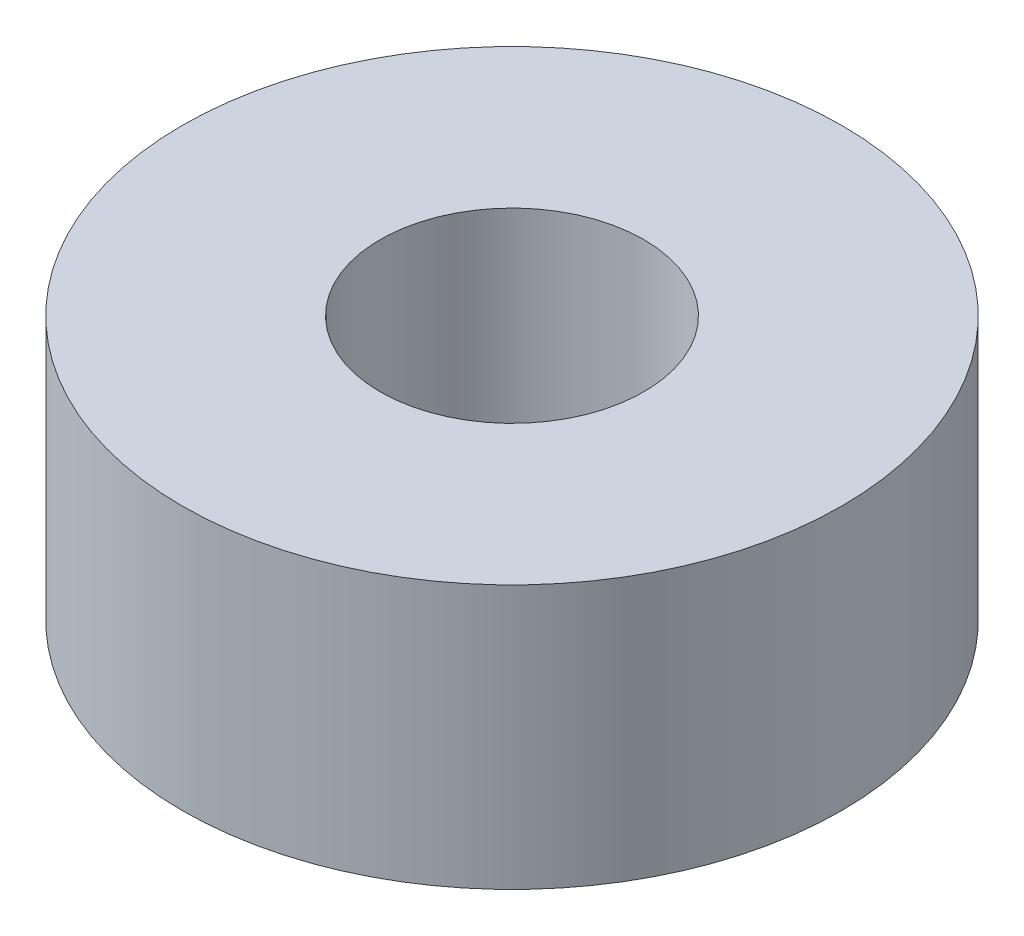
SolidWorks part; units mm, degrees
ref_plane "前视基准面" through (0, 0, 0) normal (0, 0, 1) x (1, 0, 0)
ref_plane "上视基准面" through (0, 0, 0) normal (0, 1, 0) x (1, 0, 0)
ref_plane "右视基准面" through (0, 0, 0) normal (1, 0, 0) x (0, 0, -1)
sketch "草图1" plane through (0, 0, 0) normal (0, 1, 0) x (1, 0, 0)
  circle A0 centre (0, 0) radius 2.5
  circle A1 centre (0, 0) radius 1
  dimension "D1" = 5
  dimension "D2" = 2
extrude "凸台-拉伸1" add sketch "草图1" along normal blind 2
